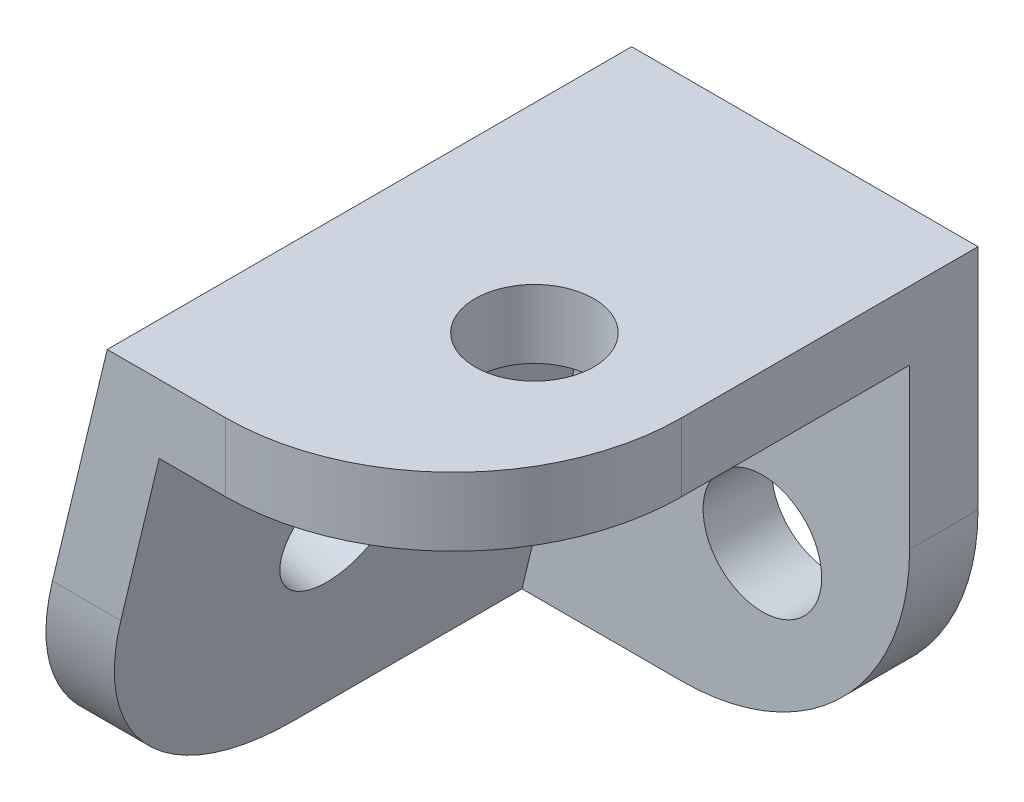
SolidWorks part; units mm, degrees
ref_plane "Plan de face" through (0, 0, 0) normal (0, 0, 1) x (1, 0, 0)
ref_plane "Plan de dessus" through (0, 0, 0) normal (0, 1, 0) x (1, 0, 0)
ref_plane "Plan de droite" through (0, 0, 0) normal (1, 0, 0) x (0, 0, -1)
sketch "Esquisse1" plane through (0, 0, 0) normal (0, 0, 1) x (1, 0, 0)
  line L0 (-44.7092, 492.3) -> (-44.7092, 472.3)
  line L1 (-8, 492.3) -> (-59.18, 492.3) construction
  line L2 (-44.7092, 472.3) -> (-64.7092, 472.3)
  line L3 (-59.18, 495.3) -> (-100, 325.5) construction
  line L4 (-64.7092, 472.3) -> (-59.9012, 492.3)
  line L5 (-59.9012, 492.3) -> (-44.7092, 492.3)
  dimension "D1" = 20
  dimension "D2" = 20
extrude "Boss.-Extru.1" add sketch "Esquisse1" along normal blind 3
ref_plane "Plan1" through (-59.18, 495.3, -3) normal (-0.2337, -0.9723, 0) x (-0.9723, 0.2337, 0)
sketch "Esquisse3" plane through (0, 0, 3) normal (0, 0, 1) x (1, 0, 0)
  line L0 (-59.9012, 492.3) -> (-64.7092, 472.3)
  line L1 (-64.7092, 472.3) -> (-61.7092, 472.3)
  line L2 (-64.7092, 472.3) -> (-44.7092, 472.3) construction
  line L3 (-61.7092, 472.3) -> (-56.9012, 492.3)
  line L4 (-44.7092, 492.3) -> (-59.9012, 492.3) construction
  line L5 (-56.9012, 492.3) -> (-59.9012, 492.3)
  dimension "D1" = 3
extrude "Boss.-Extru.2" add sketch "Esquisse3" along normal blind 20
sketch "Esquisse4" plane through (0, 0, 3) normal (0, 0, 1) x (1, 0, 0)
  line L1 (-44.7092, 492.3) -> (-59.18, 492.3)
  line L2 (-44.7092, 492.3) -> (-44.7092, 489.3)
  line L3 (-44.7092, 489.3) -> (-59.18, 489.3)
  line L4 (-59.18, 492.3) -> (-59.18, 489.3)
  point P5 (0, 0)
  dimension "D1" = 3
extrude "Boss.-Extru.3" add sketch "Esquisse4" along normal up to surface (20 mm away) up to face at (-60.8052, 482.3, 23)
fillet "Congé1" radius 10 3 edges at (-44.7092, 490.8, 23) (-44.7092, 472.3, 1.5) (-63.2092, 472.3, 23)
sketch "Esquisse5" plane through (0, 0, 3) normal (0, 0, 1) x (1, 0, 0)
  line L0 (-51.1658, 489.3) -> (-51.1658, 475.3179) construction
  line L1 (-57.6224, 489.3) -> (-44.7092, 489.3) construction
  circle A0 centre (-51.1658, 479.3) radius 2.6
  dimension "D1" = 10
  dimension "D2" = 5.2
extrude "Enlèv. mat.-Extru.1" cut sketch "Esquisse5" against normal blind 20
sketch "Esquisse6" plane through (0, 489.3, 0) normal (0, -1, 0) x (1, 0, 0)
  line L0 (-51.1658, 3) -> (-51.1658, 20.233) construction
  line L1 (-57.6224, 3) -> (-44.7092, 3) construction
  circle A0 centre (-51.1658, 13) radius 2.6
  dimension "D1" = 5.2
  dimension "D2" = 10
extrude "Enlèv. mat.-Extru.2" cut sketch "Esquisse6" against normal blind 20
sketch "Esquisse7" plane through (-165.6756, 39.8285, 0) normal (0.9723, -0.2337, 0) x (0, 0, -1)
  line L0 (-13, 462.2771) -> (-13, 444.7928) construction
  line L1 (-23, 462.2771) -> (-3, 462.2771) construction
  circle A0 centre (-13, 453.5349) radius 2.6
  dimension "D1" = 5.2
extrude "Enlèv. mat.-Extru.3" cut sketch "Esquisse7" against normal blind 20
